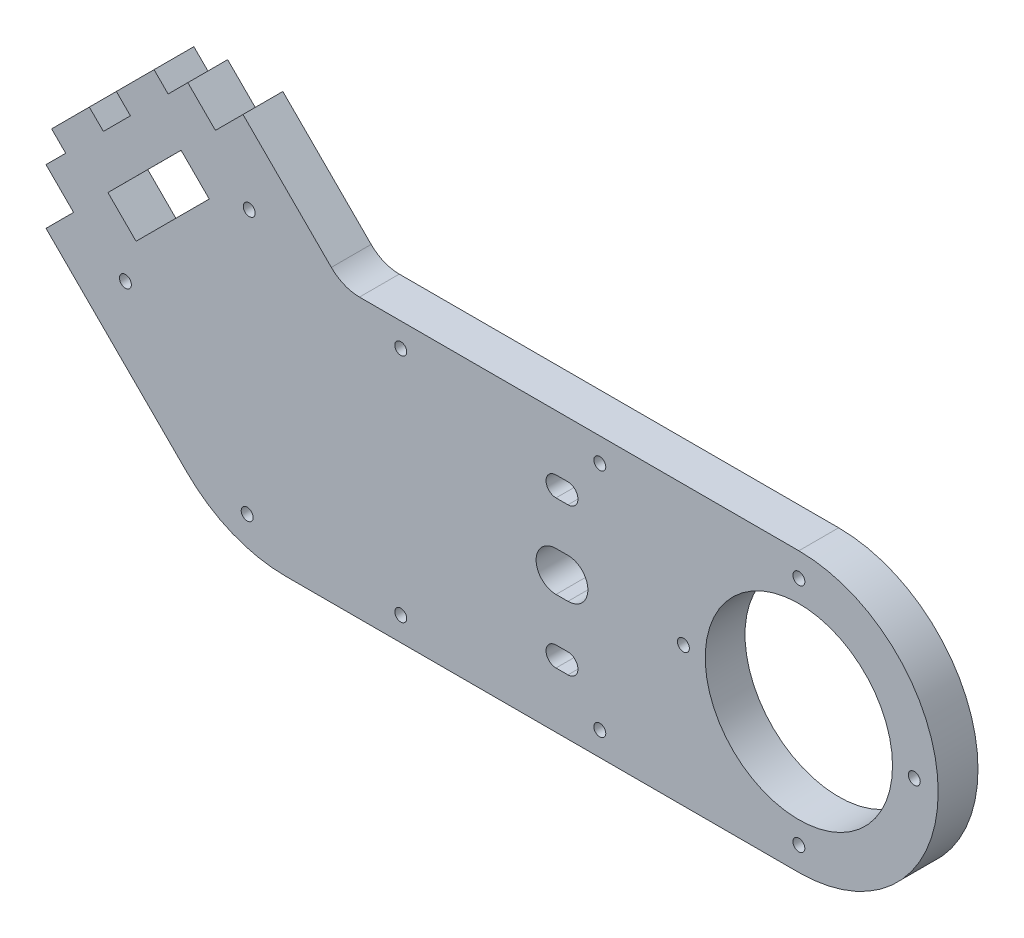
SolidWorks part; units mm, degrees
ref_plane "Front Plane" through (0, 0, 0) normal (0, 0, 1) x (1, 0, 0)
ref_plane "Top Plane" through (0, 0, 0) normal (0, 1, 0) x (1, 0, 0)
ref_plane "Right Plane" through (0, 0, 0) normal (1, 0, 0) x (0, 0, -1)
sketch "Sketch1" plane through (0, 0, 0) normal (0, 0, 1) x (1, 0, 0)
  line L0 (0, -35) -> (-129, -35)
  line L4 (0, 35) -> (-110.37, 35)
  line L9 (-58, 0) -> (-61, 0) construction
  line L10 (-58, -5) -> (-61, -5)
  line L11 (-58, 5) -> (-61, 5)
  line L13 (-58, 18.5) -> (-61, 18.5) construction
  line L14 (-58, 16) -> (-61, 16)
  line L15 (-58, 21) -> (-61, 21)
  line L17 (-58, -18.5) -> (-61, -18.5) construction
  line L18 (-58, -21) -> (-61, -21)
  line L19 (-58, -16) -> (-61, -16)
  line L25 (0, 0) -> (-129, 0) construction
  line L27 (-189.1079, 10.5847) -> (-182.1808, 17.5169)
  line L28 (-182.1808, 17.5169) -> (-146.5556, 53.168) construction
  line L29 (-146.5556, 53.168) -> (-139.6285, 60.1002)
  line L30 (-146.5556, 53.168) -> (-153.4878, 60.0952)
  line L31 (-182.1808, 17.5169) -> (-189.113, 24.444)
  line L32 (-189.113, 24.444) -> (-184.1651, 29.3955)
  line L33 (-184.1651, 29.3955) -> (-187.7019, 32.9298)
  line L34 (-153.4878, 60.0952) -> (-158.4357, 55.1436)
  line L35 (-158.4357, 55.1436) -> (-161.9726, 58.6778)
  line L36 (-187.7019, 32.9298) -> (-178.2301, 42.4085)
  line L37 (-184.1651, 29.3955) -> (-158.4357, 55.1436) construction
  line L38 (-178.2301, 42.4085) -> (-174.6933, 38.8742)
  line L39 (-161.9726, 58.6778) -> (-171.4443, 49.1992)
  line L40 (-171.4443, 49.1992) -> (-167.9075, 45.6649)
  line L41 (-174.6933, 38.8742) -> (-167.9075, 45.6649)
  line L43 (-189.1079, 10.5847) -> (-153.7397, -24.7578)
  line L44 (-171.3004, 42.2696) -> (-129, 0) construction
  line L45 (-139.6285, 60.1002) -> (-117.4393, 37.9271)
  line L46 (-173.5573, 26.1467) -> (-155.1792, 44.5382)
  line L47 (-155.1792, 44.5382) -> (-148.1081, 37.4671)
  line L48 (-148.1081, 37.4671) -> (-166.4929, 19.0823)
  line L49 (-166.4929, 19.0823) -> (-173.5573, 26.1467)
  line L54 (-129, 0) -> (-138.5766, -26.3114) construction
  circle A0 centre (0, 0) radius 23.525
  circle A1 centre (29, 0) radius 1.5
  arc A4 (0, -35) -> (0, 35) centre (0, 0) ccw
  circle A5 centre (0, 29) radius 1.5
  circle A6 centre (0, -29) radius 1.5
  circle A7 centre (-50, -29) radius 1.5
  circle A8 centre (-50, 29) radius 1.5
  circle A9 centre (-100, -29) radius 1.5
  circle A10 centre (-100, 29) radius 1.5
  arc A11 (-58, -5) -> (-58, 5) centre (-58, 0) ccw
  arc A12 (-61, 5) -> (-61, -5) centre (-61, 0) ccw
  arc A13 (-58, 16) -> (-58, 21) centre (-58, 18.5) ccw
  arc A14 (-61, 21) -> (-61, 16) centre (-61, 18.5) ccw
  arc A15 (-58, -21) -> (-58, -16) centre (-58, -18.5) ccw
  arc A16 (-61, -16) -> (-61, -21) centre (-61, -18.5) ccw
  circle A17 centre (-29, 0) radius 1.5
  arc A22 (-129, -35) -> (-153.7397, -24.7578) centre (-129, 0) cw
  arc A23 (-117.4393, 37.9271) -> (-110.37, 35) centre (-110.37, 45) ccw
  circle A27 centre (-169.167, 9.0363) radius 1.5
  circle A28 centre (-138.0656, 40.1604) radius 1.5
  circle A34 centre (-138.5766, -26.3114) radius 1.5
  point P13 (0, -29)
  point P29 (-59.5, 0)
  point P37 (-59.5, 18.5)
  point P45 (-59.5, -18.5)
  point P74 (-102.28, 58.871)
  point P79 (-122, 0)
  point P86 (-164.3682, 35.3424)
  point P91 (-155.9618, 57.6194)
  dimension "D1" = 47.05
  dimension "D4" = 70
  dimension "D5" = 3
  dimension "D6" = 3
  dimension "D7" = 3
  dimension "D8" = 3
  dimension "D9" = 3
  dimension "D10" = 3
  dimension "D11" = 3
  dimension "D14" = 50
  dimension "D12" = 35
  dimension "D13" = 35
  dimension "D19" = 5
  dimension "D22" = 36.4
  dimension "D35" = 10
  dimension "D33" = 3
  dimension "D37" = 3
  dimension "D36" = 13
  dimension "D46" = 3
  dimension "D15" = 129
  dimension "D16" = 58
  dimension "D17" = 11
  dimension "D20" = 10
  dimension "D21" = 110.37
  dimension "D23" = 50.4
  dimension "D24" = 13.4
  dimension "D25" = 9.8
  dimension "D26" = 9.8
  dimension "D27" = 7
  dimension "D28" = 9.8
  dimension "D29" = 9.8
  dimension "D30" = 5
  dimension "D31" = 5
  dimension "D32" = 13.4
  dimension "D34" = 31.3689
  dimension "D45" = 28
extrude "Boss-Extrude1" add sketch "Sketch1" along normal blind 10
